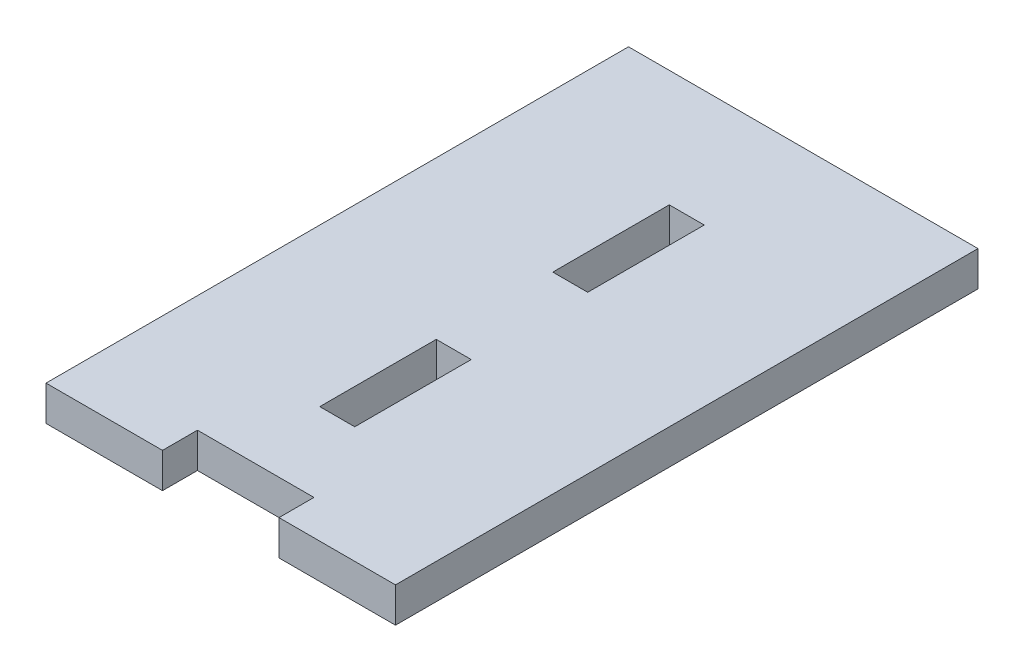
SolidWorks part; units mm, degrees
ref_plane "Alzado" through (0, 0, 0) normal (0, 0, 1) x (1, 0, 0)
ref_plane "Planta" through (0, 0, 0) normal (0, 1, 0) x (1, 0, 0)
ref_plane "Vista lateral" through (0, 0, 0) normal (1, 0, 0) x (0, 0, -1)
sketch "Croquis1" plane through (0, 0, 0) normal (0, 1, 0) x (1, 0, 0)
  line L0 (25, 0) -> (35, 0)
  line L1 (15, 3) -> (15, 0)
  line L2 (5, 0) -> (5, 50)
  line L3 (35, 0) -> (35, 50)
  line L5 (18.5, 10) -> (21.5, 10)
  line L6 (21.5, 10) -> (21.5, 20)
  line L7 (21.5, 20) -> (18.5, 20)
  line L8 (35, 50) -> (5, 50)
  line L9 (15, 3) -> (25, 3)
  line L10 (21.5, 30) -> (18.5, 30)
  line L11 (21.5, 40) -> (21.5, 30)
  line L12 (18.5, 40) -> (21.5, 40)
  line L13 (25, 3) -> (25, 0)
  line L14 (18.5, 40) -> (18.5, 30)
  line L15 (18.5, 10) -> (18.5, 20)
  line L16 (15, 0) -> (5, 0)
  point P12 (20, 50)
  dimension "D1" = 3
  dimension "D2" = 10
  dimension "D3" = 50
  dimension "D5" = 10
extrude "Saliente-Extruir1" add sketch "Croquis1" along normal blind 3
